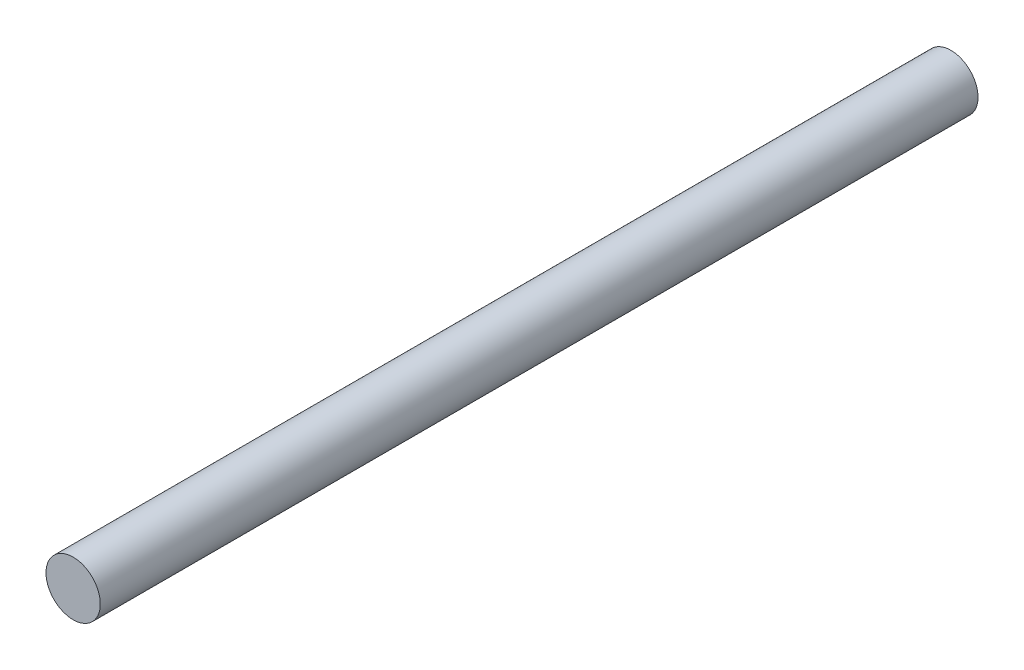
SolidWorks part; units mm, degrees
ref_plane "Front Plane" through (0, 0, 0) normal (0, 0, 1) x (1, 0, 0)
ref_plane "Top Plane" through (0, 0, 0) normal (0, 1, 0) x (1, 0, 0)
ref_plane "Right Plane" through (0, 0, 0) normal (1, 0, 0) x (0, 0, -1)
sketch "Sketch1" plane through (0, 0, 0) normal (0, 0, 1) x (1, 0, 0)
  circle A0 centre (0, 0) radius 3
extrude "Boss-Extrude1" add sketch "Sketch1" along normal blind 97
ref_plane "Plane1" through (0, 0, 81.5) normal (0, 0, 1) x (1, 0, 0)
